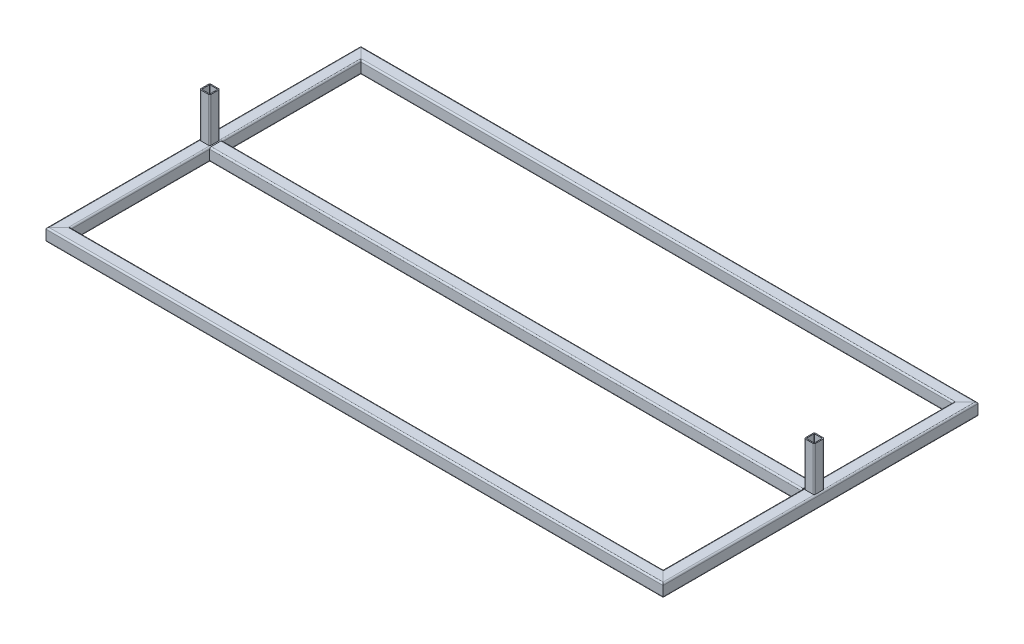
SolidWorks part; units mm, degrees
ref_plane "Спереди" through (0, 0, 0) normal (0, 0, 1) x (1, 0, 0)
ref_plane "Сверху" through (0, 0, 0) normal (0, 1, 0) x (1, 0, 0)
ref_plane "Справа" through (0, 0, 0) normal (1, 0, 0) x (0, 0, -1)
sketch "Эскиз1" plane through (0, 0, 0) normal (0, 1, 0) x (1, 0, 0)
  line L1 (-600, -300) -> (600, -300)
  line L2 (-600, -300) -> (-600, 300)
  line L3 (-600, 300) -> (600, 300)
  line L4 (600, -300) -> (600, 300)
  line L5 (0, 300) -> (0, -300) construction
  line L6 (-600, 0) -> (600, 0)
  point P0 (0, 0)
  dimension "D1" = 600
  dimension "D2" = 1200
sketch3d "Трехмерный эскиз1"
  line L0 (-600, 0, 0) -> (-600, 100, 0)
  line L1 (600, 0, 0) -> (600, 100, 0)
  dimension "D1" = 100
other "Square tube - configured 20 X 20 X 2(1)"
ref_plane "Плоскость1" through (-600, 0, -300) normal (1, 0, 0) x (0, 0, -1)
sketch "Sketch11" plane through (-600, 0, -300) normal (1, 0, 0) x (0, 0, -1)
  line L0 (-9.5, -10.5) -> (9.5, -10.5)
  line L1 (-10.5, -9.5) -> (-10.5, 9.5)
  line L2 (9.5, 10.5) -> (-9.5, 10.5)
  line L3 (10.5, 9.5) -> (10.5, -9.5)
  line L4 (-9.5, -12.5) -> (9.5, -12.5)
  line L5 (-12.5, -9.5) -> (-12.5, 9.5)
  line L6 (9.5, 12.5) -> (-9.5, 12.5)
  line L7 (12.5, 9.5) -> (12.5, -9.5)
  arc A0 (12.5, 9.5) -> (9.5, 12.5) centre (9.5, 9.5) ccw
  arc A1 (9.5, -12.5) -> (12.5, -9.5) centre (9.5, -9.5) ccw
  arc A2 (-12.5, -9.5) -> (-9.5, -12.5) centre (-9.5, -9.5) ccw
  arc A3 (-9.5, 12.5) -> (-12.5, 9.5) centre (-9.5, 9.5) ccw
  arc A4 (-9.5, 10.5) -> (-10.5, 9.5) centre (-9.5, 9.5) ccw
  arc A5 (10.5, 9.5) -> (9.5, 10.5) centre (9.5, 9.5) ccw
  arc A6 (9.5, -10.5) -> (10.5, -9.5) centre (9.5, -9.5) ccw
  arc A7 (-10.5, -9.5) -> (-9.5, -10.5) centre (-9.5, -9.5) ccw
  point P0 (-12.5, 0)
  point P1 (12.5, 0)
  point P2 (0, 12.5)
  point P3 (0, -12.5)
  point P4 (0, 0)
  point P5 (-12.5, -12.5)
  point P6 (12.5, -12.5)
  point P7 (12.5, 12.5)
  point P8 (-12.5, 12.5)
  point P33 (0, 0)
  dimension "D1" = 3
  dimension "Thickness" = 2
  dimension "V_leg" = 25
other "Square tube - configured 20 X 20 X 2(2)"
ref_plane "Плоскость2" through (-600, 0, 0) normal (0, 1, 0) x (1, 0, 0)
sketch "Sketch1" plane through (-600, 0, 0) normal (0, 1, 0) x (1, 0, 0)
  line L0 (-7.5, -8) -> (7.5, -8)
  line L1 (-8, -7.5) -> (-8, 7.5)
  line L2 (7.5, 8) -> (-7.5, 8)
  line L3 (8, 7.5) -> (8, -7.5)
  line L4 (-7.5, -10) -> (7.5, -10)
  line L5 (-10, -7.5) -> (-10, 7.5)
  line L6 (7.5, 10) -> (-7.5, 10)
  line L7 (10, 7.5) -> (10, -7.5)
  arc A0 (10, 7.5) -> (7.5, 10) centre (7.5, 7.5) ccw
  arc A1 (7.5, -10) -> (10, -7.5) centre (7.5, -7.5) ccw
  arc A2 (-10, -7.5) -> (-7.5, -10) centre (-7.5, -7.5) ccw
  arc A3 (-7.5, 10) -> (-10, 7.5) centre (-7.5, 7.5) ccw
  arc A4 (-7.5, 8) -> (-8, 7.5) centre (-7.5, 7.5) ccw
  arc A5 (8, 7.5) -> (7.5, 8) centre (7.5, 7.5) ccw
  arc A6 (7.5, -8) -> (8, -7.5) centre (7.5, -7.5) ccw
  arc A7 (-8, -7.5) -> (-7.5, -8) centre (-7.5, -7.5) ccw
  point P0 (-10, 0)
  point P1 (10, 0)
  point P2 (0, 10)
  point P3 (0, -10)
  point P4 (0, 0)
  point P5 (-10, -10)
  point P6 (10, -10)
  point P7 (10, 10)
  point P8 (-10, 10)
  point P33 (0, 0)
  dimension "D1" = 2.5
  dimension "Thickness" = 2
  dimension "V_leg" = 20
other "Отсечь/Удлинить1"
sketch "Эскиз3" plane through (0, -12.5, 0) normal (0, -1, 0) x (-1, 0, 0)
  line L0 (609.5, -309.5) -> (590.5, -290.5) construction
  circle A0 centre (600, -300) radius 6
  dimension "D1" = 12
extrude "Вырез-Вытянуть2" cut sketch "Эскиз3" against normal blind 5
mirror "Зеркальное отражение1" about plane through (0, 0, 0) normal (1, 0, 0) of "Вырез-Вытянуть2"
mirror "Зеркальное отражение2" about plane through (0, 0, 0) normal (0, 0, 1) of "Зеркальное отражение1", "Вырез-Вытянуть2"
ref_plane "Плоскость3" through (-600, 0, 0) normal (1, 0, 0) x (0, 0, -1)
